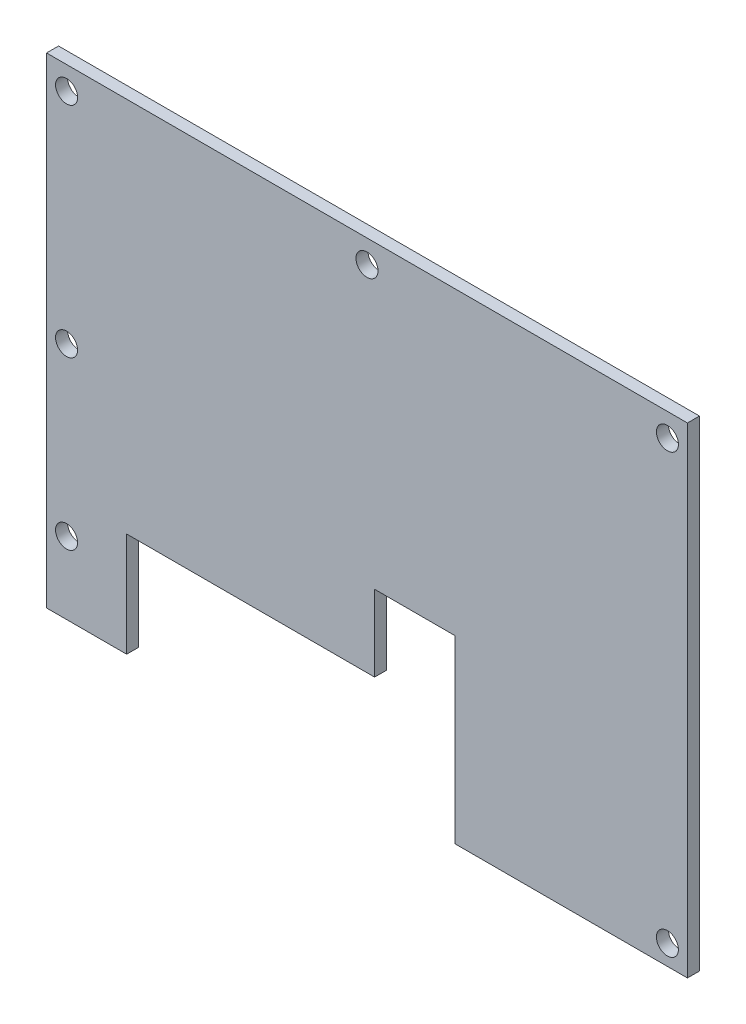
SolidWorks part; units mm, degrees
ref_plane "Front Plane" through (0, 0, 0) normal (0, 0, 1) x (1, 0, 0)
ref_plane "Top Plane" through (0, 0, 0) normal (0, 1, 0) x (1, 0, 0)
ref_plane "Right Plane" through (0, 0, 0) normal (1, 0, 0) x (0, 0, -1)
sketch "Sketch1" plane through (0, 0, 0) normal (0, 0, 1) x (1, 0, 0)
  line L1 (0, 0) -> (160, 0)
  line L2 (0, 0) -> (0, 120)
  line L3 (0, 120) -> (160, 120)
  line L4 (160, 0) -> (160, 120)
  dimension "D1" = 160
  dimension "D2" = 120
extrude "Boss-Extrude1" add sketch "Sketch1" along normal blind 3
sketch "Sketch2" plane through (0, 0, 3) normal (0, 0, 1) x (1, 0, 0)
  line L0 (0, 0) -> (160, 0) construction
  line L1 (81.9, 0) -> (102, 0)
  line L2 (81.9, 0) -> (81.9, 45)
  line L3 (81.9, 45) -> (102, 45)
  line L4 (102, 0) -> (102, 45)
  line L5 (160, 0) -> (160, 120) construction
  line L6 (0, 120) -> (0, 0) construction
  line L7 (20, 0) -> (81.9, 0)
  line L8 (20, 0) -> (20, 26)
  line L9 (20, 26) -> (81.9, 26)
  line L10 (81.9, 0) -> (81.9, 26)
  line M4 (0, 120) -> (0, 0)
  line M5 (0, 0) -> (160, 0)
  dimension "D1" = 20.1
  dimension "D2" = 58
  dimension "D3" = 45
  dimension "D4" = 26
  dimension "D5" = 20
extrude "Cut-Extrude1" cut sketch "Sketch2" against normal blind 10 contours L4 L3 L2 M5 | L9 L2 M4 M5
sketch "Sketch3" plane through (0, 0, 3) normal (0, 0, 1) x (1, 0, 0)
  line L0 (160, 0) -> (160, 120) construction
  line L1 (5, 114.23) -> (155, 114.23) construction
  line L2 (5, 114.23) -> (5, 5) construction
  line L3 (5, 5) -> (155, 5) construction
  line L4 (155, 114.23) -> (155, 5) construction
  line L6 (0, 120) -> (0, 0) construction
  line L7 (102, 0) -> (160, 0) construction
  point P0 (5, 114.23)
  point P1 (155, 5)
  point P3 (155, 114.23)
  point P6 (80, 114.23)
  point P7 (5, 59.615)
  point P12 (5, 18)
  dimension "D1" = 5
  dimension "D2" = 109.23
  dimension "D3" = 5
  dimension "D4" = 5
  dimension "D5" = 13
hole_wizard "M5 Clearance Hole1" positions "Sketch3" profile "Sketch4" hole size "M5" standard "ANSI Metric" end condition through all
sketch "Sketch4" plane through (5, 114.23, 3) normal (1, 0, 0) x (0, -1, 0)
  line L0 (0, 0) -> (0, 3)
  line L1 (0, 3) -> (2.75, 3)
  line L2 (2.75, 3) -> (2.75, 0)
  line L5 (2.75, 0) -> (0, 0)
  line L11 (0, -6.35) -> (0, 107.95) construction
  dimension "Thru Hole Dia." = 5.5
  dimension "Thru Hole Depth" = 3
